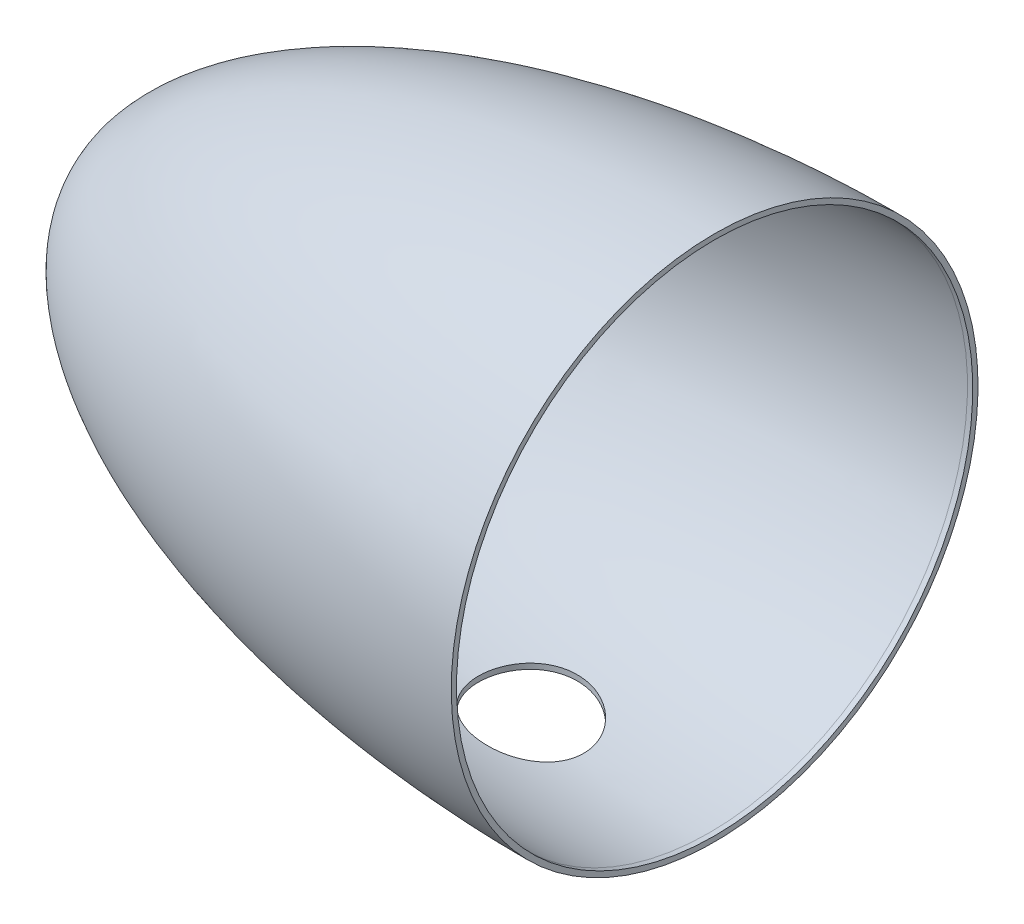
SolidWorks part; units mm, degrees
material "S-Glass Fiber"
ref_plane "Front Plane" through (0, 0, 0) normal (0, 0, 1) x (1, 0, 0)
ref_plane "Top Plane" through (0, 0, 0) normal (0, 1, 0) x (1, 0, 0)
ref_plane "Right Plane" through (0, 0, 0) normal (1, 0, 0) x (0, 0, -1)
sketch "Sketch18" plane through (0, 0, 0) normal (0, 0, 1) x (1, 0, 0)
  line L0 (0, 150) -> (0, -150) construction
  line L1 (-3, 146.9945) -> (0, 146.9945)
  line L2 (0, 0) -> (-350, 0) construction
  line L3 (-350, 0) -> (-346.9266, 0)
  line L4 (0, 150) -> (0, 146.9945)
  line L6 (-346.9266, 3) -> (-346.9266, 0)
  line L8 (-346.9266, 3) -> (-3, 3) construction
  line L9 (-350, 0) -> (0, 0) construction
  line L10 (0, 0) -> (0, 150) construction
  line L11 (-3, 3) -> (-3, 146.9945) construction
  ellipse E0 centre (0, 0) end of major axis (350, 0) minor radius 150 (-350, 0) -> (0, 150) cw
  spline S0 degree 1 poles (-346.9266, 3) (-3, 146.9945) knots 0 0 1 1 construction
  spline S1 degree 3 poles (-346.9266, 3) (-346.8137, 5.3048) (-346.3316, 9.8819) (-344.3317, 19.0575) (-339.8873, 30.4742) (-331.4324, 44.0088) (-316.046, 61.639) (-289.2947, 82.5187) (-246.3206, 104.6045) (-194.1133, 122.8093) (-144.5531, 134.1453) (-102.3921, 140.6536) (-69.8099, 144.2104) (-36.5883, 146.408) (-14.1774, 146.9533) (-3, 146.9945) knots -1.562193 -1.562193 -1.562193 -1.562193 -1.51403 -1.465867 -1.369541 -1.273216 -1.17689 -0.984238 -0.791586 -0.598935 -0.406283 -0.309957 -0.213631 -0.117305 -0.02098 -0.02098 -0.02098 -0.02098
  point P5 (0, 0)
  dimension "D1" = 150
  dimension "D2" = 350
  dimension "D3" = 3
revolve "Revolve16" add sketch "Sketch18" angle 360 about L2
sketch "Sketch19" plane through (0, 0, 0) normal (0, 1, 0) x (1, 0, 0)
  circle A0 centre (-104.5092, 0) radius 30
  dimension "D1" = 60
extrude "Cut-Extrude1" cut sketch "Sketch19" against normal blind 281
